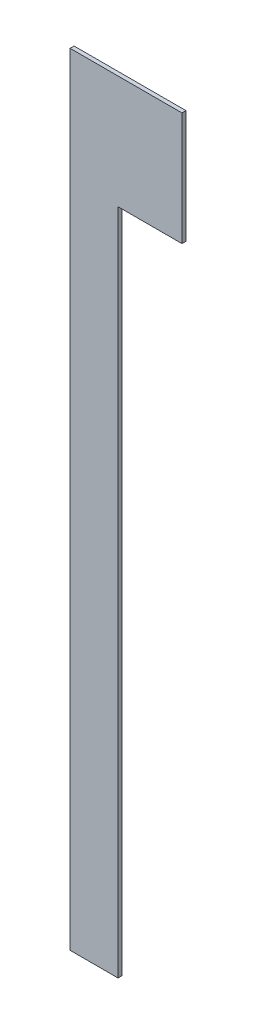
SolidWorks part; units mm, degrees
material "Гипс"
ref_plane "Спереди" through (0, 0, 0) normal (0, 0, 1) x (1, 0, 0)
ref_plane "Сверху" through (0, 0, 0) normal (0, 1, 0) x (1, 0, 0)
ref_plane "Справа" through (0, 0, 0) normal (1, 0, 0) x (0, 0, -1)
sketch "Эскиз1" plane through (0, 0, 0) normal (0, 0, 1) x (1, 0, 0)
  line L0 (150, -355) -> (950, -355) construction
  line L1 (350, -0.75) -> (0, -0.75)
  line L2 (350, -0.75) -> (350, -355)
  line L4 (0, -0.75) -> (0, -2445)
  line L5 (150, -355) -> (350, -355)
  line L6 (150, -2445) -> (150, -355) construction
  line L7 (150, -2445) -> (150, -355)
  line L8 (150, -2445) -> (0, -2445)
extrude "Бобышка-Вытянуть1" add sketch "Эскиз1" against normal blind 12.5
